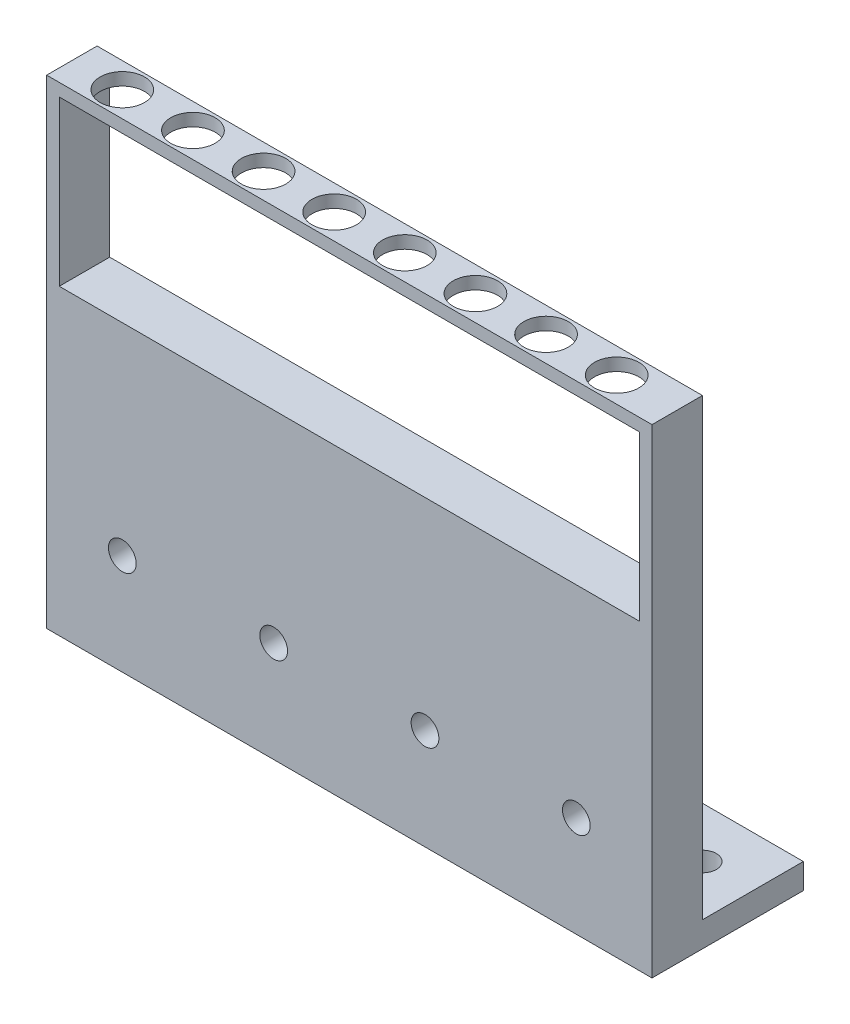
SolidWorks part; units mm, degrees
ref_plane "Front Plane" through (0, 0, 0) normal (0, 0, 1) x (1, 0, 0)
ref_plane "Top Plane" through (0, 0, 0) normal (0, 1, 0) x (1, 0, 0)
ref_plane "Right Plane" through (0, 0, 0) normal (1, 0, 0) x (0, 0, -1)
sketch "Sketch1" plane through (0, 0, 0) normal (0, 1, 0) x (1, 0, 0)
  line L1 (-76.2, -6.35) -> (76.2, -6.35)
  line L2 (-76.2, -6.35) -> (-76.2, 6.35)
  line L3 (-76.2, 6.35) -> (76.2, 6.35)
  line L4 (76.2, -6.35) -> (76.2, 6.35)
  line L5 (-76.2, -6.35) -> (76.2, 6.35) construction
  line L6 (-76.2, 6.35) -> (76.2, -6.35) construction
  point P0 (0, 0)
  dimension "D1" = 12.7
  dimension "D2" = 152.4
extrude "Boss-Extrude1" add sketch "Sketch1" along normal blind 76.2
sketch "Sketch2" plane through (0, 0, 0) normal (0, 1, 0) x (1, 0, 0)
  line L0 (-76.2, 6.35) -> (-76.2, -6.35) construction
  line L1 (-76.2, 19.05) -> (-76.2, 6.35)
  line L2 (-76.2, 6.35) -> (76.2, 6.35)
  line L3 (76.2, 31.75) -> (-76.2, 31.75)
  line L4 (-76.2, 19.05) -> (-76.2, 31.75)
  line L5 (0, 0) -> (-76.2, 31.75) construction
  line L6 (76.2, 31.75) -> (0, 0) construction
  line L7 (76.2, 6.35) -> (-76.2, 6.35) construction
  line L8 (-23.5905, 31.75) -> (-23.5905, 6.35) construction
  line L9 (-23.5905, 19.05) -> (-76.2, 19.05) construction
  line L10 (76.2, 6.35) -> (76.2, 31.75)
  circle A0 centre (-63.5, 19.05) radius 3.4925
  circle A1 centre (-38.1, 19.05) radius 3.4925
  circle A2 centre (-12.7, 19.05) radius 3.4925
  circle A3 centre (12.7, 19.05) radius 3.4925
  circle A4 centre (38.1, 19.05) radius 3.4925
  circle A5 centre (63.5, 19.05) radius 3.4925
  point P0 (0, 0)
  dimension "D2" = 6.985
  dimension "D1" = 25.4
  dimension "D3" = 6
  dimension "D4" = 12.7
extrude "Boss-Extrude4" add sketch "Sketch2" along normal blind 6.35
sketch "Sketch3" plane through (0, 0, 6.35) normal (0, 0, 1) x (1, 0, 0)
  line L0 (-76.2, 76.2) -> (-76.2, 120.65)
  line L1 (-76.2, 120.65) -> (76.2, 120.65)
  line L2 (76.2, 120.65) -> (76.2, 76.2)
  line L3 (76.2, 76.2) -> (76.2, 0) construction
  line L4 (-76.2, 76.2) -> (-76.2, 0) construction
  line L5 (76.2, 76.2) -> (73.025, 76.2)
  line L6 (-76.2, 76.2) -> (76.2, 76.2) construction
  line L7 (73.025, 76.2) -> (73.025, 117.475)
  line L8 (73.025, 117.475) -> (-73.025, 117.475)
  line L9 (-73.025, 117.475) -> (-73.025, 76.2)
  line L10 (-73.025, 76.2) -> (-76.2, 76.2)
  line L11 (-73.025, 117.475) -> (-73.025, 120.65) construction
  dimension "D1" = 3.175
  dimension "D2" = 44.45
extrude "Boss-Extrude5" add sketch "Sketch3" against normal up to surface (12.7 mm away) up to face at (0, 41.275, -6.35)
sketch "Sketch4" plane through (0, 120.65, 0) normal (0, 1, 0) x (1, 0, 0)
  line L0 (-76.2, 6.35) -> (-76.2, -6.35) construction
  circle A0 centre (-63.5, 0) radius 5.588
  circle A1 centre (-45.72, 0) radius 5.588
  circle A2 centre (-27.94, 0) radius 5.588
  circle A3 centre (-10.16, 0) radius 5.588
  circle A4 centre (7.62, 0) radius 5.588
  circle A5 centre (25.4, 0) radius 5.588
  circle A6 centre (43.18, 0) radius 5.588
  circle A7 centre (60.96, 0) radius 5.588
  dimension "D1" = 11.176
  dimension "D2" = 12.7
  dimension "D3" = 8
extrude "Cut-Extrude1" cut sketch "Sketch4" against normal up to next
sketch "Sketch5" plane through (0, 0, -6.35) normal (0, 0, -1) x (-1, 0, 0)
  line L0 (-76.2, 0) -> (76.2, 0) construction
  line L1 (-76.2, 6.35) -> (-76.2, 0) construction
  circle A0 centre (-57.15, 25.4) radius 3.4925
  circle A1 centre (-19.05, 25.4) radius 3.4925
  circle A2 centre (19.05, 25.4) radius 3.4925
  circle A3 centre (57.15, 25.4) radius 3.4925
  dimension "D2" = 6.985
  dimension "D1" = 25.4
  dimension "D3" = 19.05
  dimension "D4" = 4
extrude "Cut-Extrude2" cut sketch "Sketch5" against normal through all
